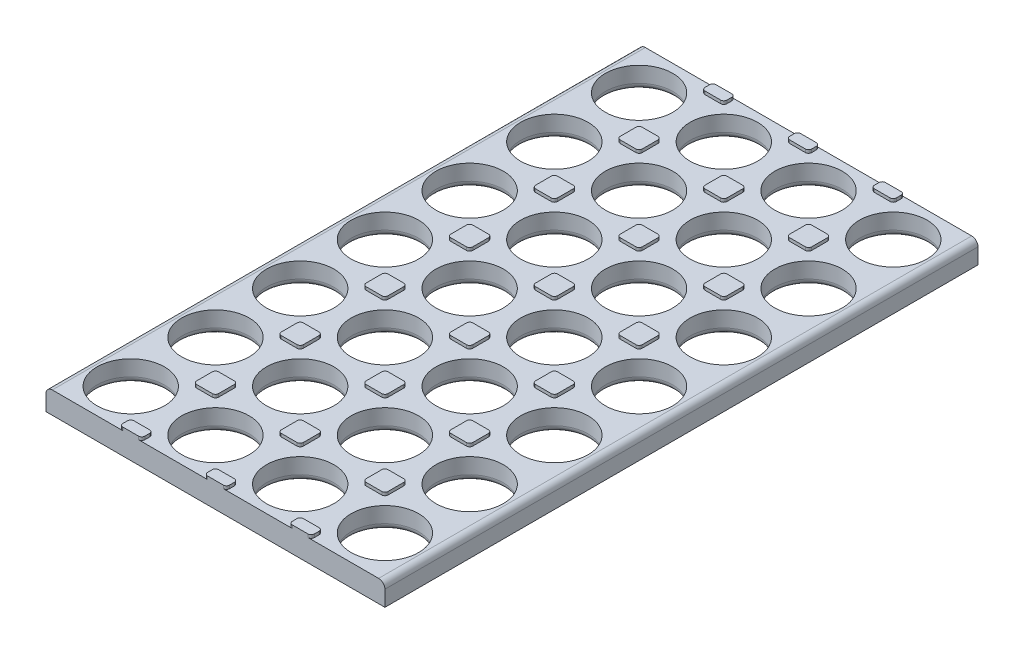
SolidWorks part; units mm, degrees
ref_plane "Front Plane" through (0, 0, 0) normal (0, 0, 1) x (1, 0, 0)
ref_plane "Top Plane" through (0, 0, 0) normal (0, 1, 0) x (1, 0, 0)
ref_plane "Right Plane" through (0, 0, 0) normal (1, 0, 0) x (0, 0, -1)
sketch "Sketch1" plane through (0, 0, 0) normal (0, 1, 0) x (1, 0, 0)
  line L0 (13.5, 27) -> (13.5, 0) construction
  line L1 (0, 0) -> (27, 0) construction
  line L2 (0, 0) -> (0, 27) construction
  line L3 (0, 27) -> (27, 27) construction
  line L4 (27, 0) -> (27, 27) construction
  line L5 (0, 13.5) -> (27, 13.5) construction
  line L6 (13.5, 13.5) -> (13.5, 40.5) construction
  line L7 (0, 0) -> (108, 0)
  line L8 (0, 0) -> (0, 189)
  line L9 (0, 189) -> (108, 189)
  line L10 (108, 0) -> (108, 189)
  circle A0 centre (13.5, 13.5) radius 10.75
  circle A1 centre (40.5, 13.5) radius 10.75
  circle A2 centre (67.5, 13.5) radius 10.75
  circle A3 centre (94.5, 13.5) radius 10.75
  circle A4 centre (40.5, 40.5) radius 10.75
  circle A5 centre (67.5, 40.5) radius 10.75
  circle A6 centre (94.5, 40.5) radius 10.75
  circle A7 centre (40.5, 67.5) radius 10.75
  circle A8 centre (67.5, 67.5) radius 10.75
  circle A9 centre (94.5, 67.5) radius 10.75
  circle A10 centre (40.5, 94.5) radius 10.75
  circle A11 centre (67.5, 94.5) radius 10.75
  circle A12 centre (94.5, 94.5) radius 10.75
  circle A13 centre (40.5, 121.5) radius 10.75
  circle A14 centre (67.5, 121.5) radius 10.75
  circle A15 centre (94.5, 121.5) radius 10.75
  circle A16 centre (40.5, 148.5) radius 10.75
  circle A17 centre (67.5, 148.5) radius 10.75
  circle A18 centre (94.5, 148.5) radius 10.75
  circle A19 centre (40.5, 175.5) radius 10.75
  circle A20 centre (67.5, 175.5) radius 10.75
  circle A21 centre (94.5, 175.5) radius 10.75
  circle A22 centre (13.5, 40.5) radius 10.75
  circle A23 centre (13.5, 67.5) radius 10.75
  circle A24 centre (13.5, 94.5) radius 10.75
  circle A25 centre (13.5, 121.5) radius 10.75
  circle A26 centre (13.5, 148.5) radius 10.75
  circle A27 centre (13.5, 175.5) radius 10.75
  point P68 (0, 0)
  dimension "D3" = 21.5
  dimension "D1" = 27
  dimension "D2" = 27
  dimension "D6" = 189
  dimension "D7" = 108
  dimension "D8" = 27
  dimension "D9" = 27
  dimension "D4" = 4
  dimension "D5" = 7
extrude "main-body" add sketch "Sketch1" along normal blind 7
sketch "Sketch2" plane through (0, 7, 0) normal (0, 1, 0) x (1, 0, 0)
  line L5 (0, 189) -> (0, 0) construction
  line L6 (108, 189) -> (0, 189) construction
  line L7 (50.5, 0) -> (50.5, 3.5)
  line L8 (23.5, -3.5) -> (30.5, -3.5)
  line L10 (57.5, 0) -> (57.5, 3.5)
  line L26 (23.5, -3.5) -> (23.5, 3.5)
  line L27 (23.5, 3.5) -> (30.5, 3.5)
  line L28 (30.5, -3.5) -> (30.5, 3.5)
  line L29 (50.5, 3.5) -> (57.5, 3.5)
  line L30 (77.5, 0) -> (77.5, 3.5)
  line L32 (84.5, 0) -> (84.5, 3.5)
  line L33 (77.5, 3.5) -> (84.5, 3.5)
  line L34 (50.5, 23.5) -> (50.5, 30.5)
  line L35 (50.5, 23.5) -> (57.5, 23.5)
  line L36 (57.5, 23.5) -> (57.5, 30.5)
  line L37 (50.5, 30.5) -> (57.5, 30.5)
  line L38 (77.5, 23.5) -> (77.5, 30.5)
  line L39 (77.5, 23.5) -> (84.5, 23.5)
  line L40 (84.5, 23.5) -> (84.5, 30.5)
  line L41 (77.5, 30.5) -> (84.5, 30.5)
  line L42 (50.5, 50.5) -> (50.5, 57.5)
  line L43 (50.5, 50.5) -> (57.5, 50.5)
  line L44 (57.5, 50.5) -> (57.5, 57.5)
  line L45 (50.5, 57.5) -> (57.5, 57.5)
  line L46 (77.5, 50.5) -> (77.5, 57.5)
  line L47 (77.5, 50.5) -> (84.5, 50.5)
  line L48 (84.5, 50.5) -> (84.5, 57.5)
  line L49 (77.5, 57.5) -> (84.5, 57.5)
  line L50 (50.5, 77.5) -> (50.5, 84.5)
  line L51 (50.5, 77.5) -> (57.5, 77.5)
  line L52 (57.5, 77.5) -> (57.5, 84.5)
  line L53 (50.5, 84.5) -> (57.5, 84.5)
  line L54 (77.5, 77.5) -> (77.5, 84.5)
  line L55 (77.5, 77.5) -> (84.5, 77.5)
  line L56 (84.5, 77.5) -> (84.5, 84.5)
  line L57 (77.5, 84.5) -> (84.5, 84.5)
  line L58 (50.5, 104.5) -> (50.5, 111.5)
  line L59 (50.5, 104.5) -> (57.5, 104.5)
  line L60 (57.5, 104.5) -> (57.5, 111.5)
  line L61 (50.5, 111.5) -> (57.5, 111.5)
  line L62 (77.5, 104.5) -> (77.5, 111.5)
  line L63 (77.5, 104.5) -> (84.5, 104.5)
  line L64 (84.5, 104.5) -> (84.5, 111.5)
  line L65 (77.5, 111.5) -> (84.5, 111.5)
  line L66 (50.5, 131.5) -> (50.5, 138.5)
  line L67 (50.5, 131.5) -> (57.5, 131.5)
  line L68 (57.5, 131.5) -> (57.5, 138.5)
  line L69 (50.5, 138.5) -> (57.5, 138.5)
  line L70 (77.5, 131.5) -> (77.5, 138.5)
  line L71 (77.5, 131.5) -> (84.5, 131.5)
  line L72 (84.5, 131.5) -> (84.5, 138.5)
  line L73 (77.5, 138.5) -> (84.5, 138.5)
  line L74 (50.5, 158.5) -> (50.5, 165.5)
  line L75 (50.5, 158.5) -> (57.5, 158.5)
  line L76 (57.5, 158.5) -> (57.5, 165.5)
  line L77 (50.5, 165.5) -> (57.5, 165.5)
  line L78 (77.5, 158.5) -> (77.5, 165.5)
  line L79 (77.5, 158.5) -> (84.5, 158.5)
  line L80 (84.5, 158.5) -> (84.5, 165.5)
  line L81 (77.5, 165.5) -> (84.5, 165.5)
  line L82 (50.5, 185.5) -> (50.5, 189)
  line L83 (50.5, 185.5) -> (57.5, 185.5)
  line L84 (57.5, 185.5) -> (57.5, 189)
  line L86 (77.5, 185.5) -> (77.5, 189)
  line L87 (77.5, 185.5) -> (84.5, 185.5)
  line L88 (84.5, 185.5) -> (84.5, 189)
  line L90 (23.5, 23.5) -> (23.5, 30.5)
  line L91 (23.5, 23.5) -> (30.5, 23.5)
  line L92 (30.5, 23.5) -> (30.5, 30.5)
  line L93 (23.5, 30.5) -> (30.5, 30.5)
  line L94 (23.5, 50.5) -> (23.5, 57.5)
  line L95 (23.5, 50.5) -> (30.5, 50.5)
  line L96 (30.5, 50.5) -> (30.5, 57.5)
  line L97 (23.5, 57.5) -> (30.5, 57.5)
  line L98 (23.5, 77.5) -> (23.5, 84.5)
  line L99 (23.5, 77.5) -> (30.5, 77.5)
  line L100 (30.5, 77.5) -> (30.5, 84.5)
  line L101 (23.5, 84.5) -> (30.5, 84.5)
  line L102 (23.5, 104.5) -> (23.5, 111.5)
  line L103 (23.5, 104.5) -> (30.5, 104.5)
  line L104 (30.5, 104.5) -> (30.5, 111.5)
  line L105 (23.5, 111.5) -> (30.5, 111.5)
  line L106 (23.5, 131.5) -> (23.5, 138.5)
  line L107 (23.5, 131.5) -> (30.5, 131.5)
  line L108 (30.5, 131.5) -> (30.5, 138.5)
  line L109 (23.5, 138.5) -> (30.5, 138.5)
  line L110 (23.5, 158.5) -> (23.5, 165.5)
  line L111 (23.5, 158.5) -> (30.5, 158.5)
  line L112 (30.5, 158.5) -> (30.5, 165.5)
  line L113 (23.5, 165.5) -> (30.5, 165.5)
  line L114 (23.5, 185.5) -> (23.5, 189)
  line L115 (23.5, 185.5) -> (30.5, 185.5)
  line L116 (30.5, 185.5) -> (30.5, 189)
  line L118 (0, 0) -> (108, 0) construction
  line L119 (23.5, 0) -> (84.5, 0)
  line L122 (84.5, 189) -> (23.5, 189)
  line L123 (77.5, -3.5) -> (84.5, -3.5) [skipped]
  line L124 (50.5, -3.5) -> (57.5, -3.5) [skipped]
  line L125 (77.5, 192.5) -> (84.5, 192.5) [skipped]
  line L126 (50.5, 192.5) -> (57.5, 192.5) [skipped]
  line L127 (23.5, 192.5) -> (30.5, 192.5) [skipped]
  point P4 (101.4767, 192.5)
  point P7 (30.5, 0)
  point P72 (84.5, 189)
  point P101 (77.5, 189)
  point P103 (30.5, 27)
  point P104 (27, 23.5)
  point P119 (77.5, 185.5)
  dimension "D1" = 7
  dimension "D2" = 23.5
  dimension "D3" = 3
  dimension "D4" = 8
  dimension "D5" = 27
  dimension "D6" = 27
  dimension "D7" = 27
extrude "bottom-stopper" add sketch "Sketch2" along normal blind 1 contours L26 L119 L28 L27 | L7 L119 L10 L29 | L30 L119 L32 L33 | L41 L38 L39 L40 | L37 L34 L35 L36 | L93 L90 L91 L92 | L97 L94 L95 L96 | L45 L42 L43 L44 | L49 L46 L47 L48 | L57 L54 L55 L56 | L53 L50 L51 L52 | L105 L102 L103 L104 | L61 L58 L59 L60 | L65 L62 L63 L64 | L73 L70 L71 L72 | L69 L66 L67 L68 | L109 L106 L107 L108 | L113 L110 L111 L112 | L77 L74 L75 L76 | L81 L78 L79 L80 | L88 L122 L86 L87 | L84 L122 L82 L83 | L116 L122 L114 L115 | L100 L101 L98 L99
fillet "Fillet1" radius 1 96 edges at (30.5, 7.5, -77.5) (30.5, 7.5, -84.5) (23.5, 7.5, -84.5) (23.5, 7.5, -77.5) (23.5, 7.5, -158.5) (30.5, 7.5, -158.5) (30.5, 7.5, -165.5) (23.5, 7.5, -165.5) (50.5, 7.5, -158.5) (57.5, 7.5, -158.5) (57.5, 7.5, -165.5) (50.5, 7.5, -165.5) (77.5, 7.5, -158.5) (84.5, 7.5, -158.5) (84.5, 7.5, -165.5) (77.5, 7.5, -165.5) (57.5, 7.5, -3.5) (57.5, 7.5, 0) (50.5, 7.5, -3.5) (50.5, 7.5, 0) (30.5, 7.5, -3.5) (30.5, 7.5, 0) (23.5, 7.5, -3.5) (23.5, 7.5, 0) (23.5, 7.5, -185.5) (23.5, 7.5, -189) (30.5, 7.5, -185.5) (30.5, 7.5, -189) (50.5, 7.5, -185.5) (50.5, 7.5, -189) (57.5, 7.5, -185.5) (57.5, 7.5, -189) (77.5, 7.5, -185.5) (77.5, 7.5, -189) (84.5, 7.5, -185.5) (84.5, 7.5, -189) (84.5, 7.5, -3.5) (84.5, 7.5, 0) (77.5, 7.5, -3.5) (77.5, 7.5, 0) (77.5, 7.5, -77.5) (84.5, 7.5, -77.5) (84.5, 7.5, -84.5) (77.5, 7.5, -84.5) (50.5, 7.5, -77.5) (57.5, 7.5, -77.5) (57.5, 7.5, -84.5) (50.5, 7.5, -84.5) (23.5, 7.5, -104.5) (30.5, 7.5, -104.5) (30.5, 7.5, -111.5) (23.5, 7.5, -111.5) (50.5, 7.5, -104.5) (57.5, 7.5, -104.5) (57.5, 7.5, -111.5) (50.5, 7.5, -111.5) (77.5, 7.5, -104.5) (84.5, 7.5, -104.5) (84.5, 7.5, -111.5) (77.5, 7.5, -111.5) (77.5, 7.5, -131.5) (84.5, 7.5, -131.5) (84.5, 7.5, -138.5) (77.5, 7.5, -138.5) (50.5, 7.5, -131.5) (57.5, 7.5, -131.5) (57.5, 7.5, -138.5) (50.5, 7.5, -138.5) (23.5, 7.5, -131.5) (30.5, 7.5, -131.5) (30.5, 7.5, -138.5) (23.5, 7.5, -138.5) (77.5, 7.5, -23.5) (84.5, 7.5, -23.5) (84.5, 7.5, -30.5) (77.5, 7.5, -30.5) (50.5, 7.5, -23.5) (57.5, 7.5, -23.5) (57.5, 7.5, -30.5) (50.5, 7.5, -30.5) (23.5, 7.5, -23.5) (30.5, 7.5, -23.5) (30.5, 7.5, -30.5) (23.5, 7.5, -30.5) (30.5, 7.5, -50.5) (30.5, 7.5, -57.5) (23.5, 7.5, -57.5) (50.5, 7.5, -50.5) (57.5, 7.5, -50.5) (57.5, 7.5, -57.5) (50.5, 7.5, -57.5) (77.5, 7.5, -50.5) (84.5, 7.5, -50.5) (84.5, 7.5, -57.5) (77.5, 7.5, -57.5) (23.5, 7.5, -50.5)
fillet "Fillet2" radius 2 30 edges at (108, 7, -94.5) (0, 7, -94.5) (13.5, 0, -164.75) (13.5, 0, -110.75) (13.5, 0, -56.75) (40.5, 0, -164.75) (67.5, 0, -137.75) (94.5, 0, -110.75) (40.5, 0, -110.75) (67.5, 0, -83.75) (94.5, 0, -56.75) (40.5, 0, -56.75) (67.5, 0, -29.75) (94.5, 0, -2.75) (40.5, 0, -2.75) (13.5, 0, -2.75) (67.5, 0, -2.75) (40.5, 0, -29.75) (94.5, 0, -29.75) (67.5, 0, -56.75) (40.5, 0, -83.75) (94.5, 0, -83.75) (67.5, 0, -110.75) (40.5, 0, -137.75) (94.5, 0, -137.75) (67.5, 0, -164.75) (13.5, 0, -29.75) (13.5, 0, -83.75) (13.5, 0, -137.75) (94.5, 0, -164.75)
